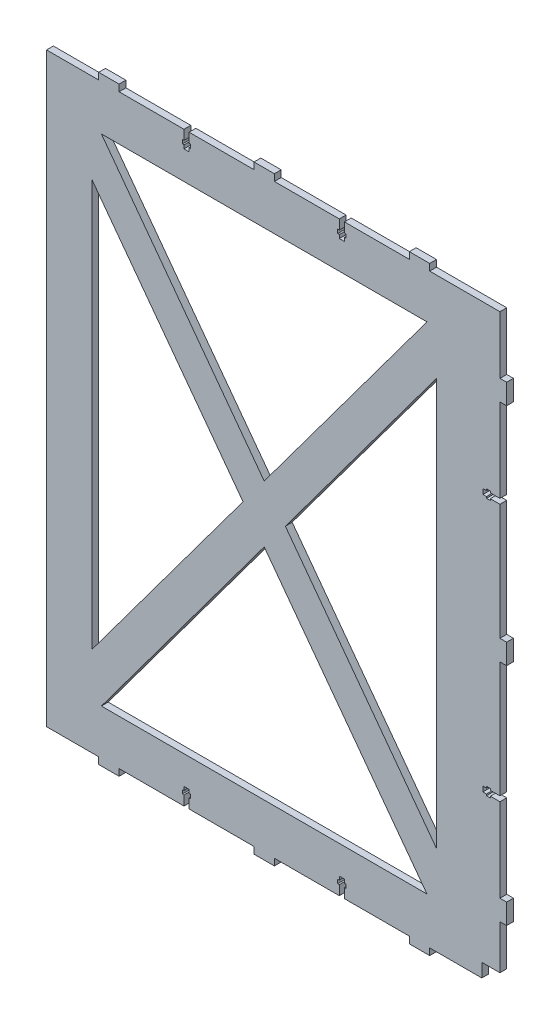
SolidWorks part; units mm, degrees
ref_plane "Спереди" through (0, 0, 0) normal (0, 0, 1) x (1, 0, 0)
ref_plane "Сверху" through (0, 0, 0) normal (0, 1, 0) x (1, 0, 0)
ref_plane "Справа" through (0, 0, 0) normal (1, 0, 0) x (0, 0, -1)
sketch "Эскиз1" plane through (0, 0, 0) normal (0, 0, 1) x (1, 0, 0)
  line L0 (624.2, 179.5716) -> (490.7832, -0.1)
  line L1 (664.2, 258.6) -> (280, 258.6)
  line L2 (664.2, 258.6) -> (664.2, -258.8)
  line L3 (664.2, -258.8) -> (280, -258.8)
  line L4 (280, 258.6) -> (280, -258.8)
  line L5 (615.8144, 218.6) -> (472.1, 25.0606)
  line L6 (615.8144, 218.6) -> (328.3856, 218.6)
  line L7 (624.2, 179.5716) -> (624.2, -179.7716)
  line L8 (615.8144, -218.8) -> (328.3856, -218.8)
  line L9 (320, 179.5716) -> (320, -179.7716)
  line L10 (624.2, -179.7716) -> (490.7832, -0.1)
  line L11 (615.8144, -218.8) -> (472.1, -25.2606)
  line L12 (472.1, 25.0606) -> (328.3856, 218.6)
  line L13 (453.4168, -0.1) -> (320, 179.5716)
  line L14 (453.4168, -0.1) -> (320, -179.7716)
  line L15 (472.1, -25.2606) -> (328.3856, -218.8)
  line L16 (620.0072, 199.0858) -> (664.2, 258.6) construction
  line L17 (490.7832, -0.1) -> (453.4168, -0.1) construction
  line L18 (472.1, 25.0606) -> (472.1, -25.2606) construction
  line L19 (624.2, 179.5716) -> (615.8144, 218.6) construction
  line L20 (320, -179.7716) -> (328.3856, -218.8) construction
  line L21 (324.1928, -199.2858) -> (620.0072, 199.0858) construction
  line L22 (328.3856, 218.6) -> (320, 179.5716) construction
  line L23 (624.2, -179.7716) -> (615.8144, -218.8) construction
  line L24 (620.0072, -199.2858) -> (324.1928, 199.0858) construction
  point P20 (472.1, -0.1)
  point P21 (472.1, -0.1)
  point P25 (472.1, -0.1)
  dimension "D1" = 40
  dimension "D2" = 40
  dimension "D3" = 40
  dimension "D4" = 40
  dimension "D5" = 30
extrude "Бобышка-Вытянуть1" add sketch "Эскиз1" along normal blind 6 and the other way blind 0.0001
sketch "Шипы боковой стенки к основаниям — эскиз" plane through (0, 0, 0) normal (0, 0, 1) x (1, 0, 0)
  line L0 (326, -264.7) -> (344, -264.7)
  line L1 (344, -264.7) -> (344, -258.5)
  line L2 (344, -258.5) -> (326, -258.5)
  line L3 (326, -258.5) -> (326, -264.7)
  line L4 (463.1, -264.7) -> (481.1, -264.7)
  line L5 (481.1, -264.7) -> (481.1, -258.5)
  line L6 (481.1, -258.5) -> (463.1, -258.5)
  line L7 (463.1, -258.5) -> (463.1, -264.7)
  line L8 (600.2, -264.7) -> (618.2, -264.7)
  line L9 (618.2, -264.7) -> (618.2, -258.5)
  line L10 (618.2, -258.5) -> (600.2, -258.5)
  line L11 (600.2, -258.5) -> (600.2, -264.7)
  line L12 (326, 258.3) -> (344, 258.3)
  line L13 (344, 258.3) -> (344, 264.5)
  line L14 (344, 264.5) -> (326, 264.5)
  line L15 (326, 264.5) -> (326, 258.3)
  line L16 (463.1, 258.3) -> (481.1, 258.3)
  line L17 (481.1, 258.3) -> (481.1, 264.5)
  line L18 (481.1, 264.5) -> (463.1, 264.5)
  line L19 (463.1, 264.5) -> (463.1, 258.3)
  line L20 (600.2, 258.3) -> (618.2, 258.3)
  line L21 (618.2, 258.3) -> (618.2, 264.5)
  line L22 (618.2, 264.5) -> (600.2, 264.5)
  line L23 (600.2, 264.5) -> (600.2, 258.3)
  dimension "X001" = 326
  dimension "X002" = 344
  dimension "X003" = 463.1
  dimension "X004" = 481.1
  dimension "X005" = 600.2
  dimension "X006" = 618.2
  dimension "Y001" = 264.7
  dimension "Y002" = 258.5
  dimension "Y003" = 258.3
  dimension "Y004" = 264.5
extrude "Шипы боковой стенки к основаниям" add sketch "Шипы боковой стенки к основаниям — эскиз" along normal blind 6
sketch "Карманные стяжки М4 к основаниям — эскиз" plane through (0, 0, 0) normal (0, 0, 1) x (1, 0, 0)
  line L0 (401.3, -259.8) -> (405.8, -259.8)
  line L1 (405.8, -259.8) -> (405.8, -250.3)
  line L2 (405.8, -250.3) -> (407.2, -250.3)
  line L3 (407.2, -250.3) -> (407.2, -246.9)
  line L4 (407.2, -246.9) -> (405.8, -246.9)
  line L5 (405.8, -246.9) -> (405.8, -243.8)
  line L6 (405.8, -243.8) -> (401.3, -243.8)
  line L7 (401.3, -243.8) -> (401.3, -246.9)
  line L8 (401.3, -246.9) -> (399.9, -246.9)
  line L9 (399.9, -246.9) -> (399.9, -250.3)
  line L10 (399.9, -250.3) -> (401.3, -250.3)
  line L11 (401.3, -250.3) -> (401.3, -259.8)
  line L12 (538.4, -259.8) -> (542.9, -259.8)
  line L13 (542.9, -259.8) -> (542.9, -250.3)
  line L14 (542.9, -250.3) -> (544.3, -250.3)
  line L15 (544.3, -250.3) -> (544.3, -246.9)
  line L16 (544.3, -246.9) -> (542.9, -246.9)
  line L17 (542.9, -246.9) -> (542.9, -243.8)
  line L18 (542.9, -243.8) -> (538.4, -243.8)
  line L19 (538.4, -243.8) -> (538.4, -246.9)
  line L20 (538.4, -246.9) -> (537, -246.9)
  line L21 (537, -246.9) -> (537, -250.3)
  line L22 (537, -250.3) -> (538.4, -250.3)
  line L23 (538.4, -250.3) -> (538.4, -259.8)
  line L24 (401.3, 259.6) -> (405.8, 259.6)
  line L25 (405.8, 259.6) -> (405.8, 250.1)
  line L26 (405.8, 250.1) -> (407.2, 250.1)
  line L27 (407.2, 250.1) -> (407.2, 246.7)
  line L28 (407.2, 246.7) -> (405.8, 246.7)
  line L29 (405.8, 246.7) -> (405.8, 243.6)
  line L30 (405.8, 243.6) -> (401.3, 243.6)
  line L31 (401.3, 243.6) -> (401.3, 246.7)
  line L32 (401.3, 246.7) -> (399.9, 246.7)
  line L33 (399.9, 246.7) -> (399.9, 250.1)
  line L34 (399.9, 250.1) -> (401.3, 250.1)
  line L35 (401.3, 250.1) -> (401.3, 259.6)
  line L36 (538.4, 259.6) -> (542.9, 259.6)
  line L37 (542.9, 259.6) -> (542.9, 250.1)
  line L38 (542.9, 250.1) -> (544.3, 250.1)
  line L39 (544.3, 250.1) -> (544.3, 246.7)
  line L40 (544.3, 246.7) -> (542.9, 246.7)
  line L41 (542.9, 246.7) -> (542.9, 243.6)
  line L42 (542.9, 243.6) -> (538.4, 243.6)
  line L43 (538.4, 243.6) -> (538.4, 246.7)
  line L44 (538.4, 246.7) -> (537, 246.7)
  line L45 (537, 246.7) -> (537, 250.1)
  line L46 (537, 250.1) -> (538.4, 250.1)
  line L47 (538.4, 250.1) -> (538.4, 259.6)
  dimension "X001" = 399.9
  dimension "X002" = 401.3
  dimension "X003" = 405.8
  dimension "X004" = 407.2
  dimension "X005" = 537
  dimension "X006" = 538.4
  dimension "X007" = 542.9
  dimension "X008" = 544.3
  dimension "Y001" = 259.8
  dimension "Y002" = 250.3
  dimension "Y003" = 246.9
  dimension "Y004" = 243.8
  dimension "Y005" = 243.6
  dimension "Y006" = 246.7
  dimension "Y007" = 250.1
  dimension "Y008" = 259.6
extrude "Карманные стяжки М4 к основаниям" cut sketch "Карманные стяжки М4 к основаниям — эскиз" against normal through all and the other way through all
sketch "Задние стойки боковых стенок — эскиз" plane through (0, 0, 0) normal (0, 0, 1) x (1, 0, 0)
  line L0 (663.2, -246.8) -> (680.2, -246.8)
  line L1 (680.2, -246.8) -> (680.2, 258.6)
  line L2 (680.2, 258.6) -> (663.2, 258.6)
  line L3 (663.2, 258.6) -> (663.2, -246.8)
  dimension "X001" = 663.2
  dimension "X002" = 680.2
  dimension "Y001" = 246.8
  dimension "Y002" = 258.6
extrude "Задние стойки боковых стенок" add sketch "Задние стойки боковых стенок — эскиз" along normal blind 6
sketch "Задние шипы боковой стенки — эскиз" plane through (0, 0, 0) normal (0, 0, 1) x (1, 0, 0)
  line L0 (679.9, -207.8) -> (686.1, -207.8)
  line L1 (686.1, -207.8) -> (686.1, -189.8)
  line L2 (686.1, -189.8) -> (679.9, -189.8)
  line L3 (679.9, -189.8) -> (679.9, -207.8)
  line L4 (679.9, -9.1) -> (686.1, -9.1)
  line L5 (686.1, -9.1) -> (686.1, 8.9)
  line L6 (686.1, 8.9) -> (679.9, 8.9)
  line L7 (679.9, 8.9) -> (679.9, -9.1)
  line L8 (679.9, 189.6) -> (686.1, 189.6)
  line L9 (686.1, 189.6) -> (686.1, 207.6)
  line L10 (686.1, 207.6) -> (679.9, 207.6)
  line L11 (679.9, 207.6) -> (679.9, 189.6)
  dimension "X001" = 679.9
  dimension "X002" = 686.1
  dimension "Y001" = 207.8
  dimension "Y002" = 189.8
  dimension "Y003" = 9.1
  dimension "Y004" = 8.9
  dimension "Y005" = 189.6
  dimension "Y006" = 207.6
extrude "Задние шипы боковой стенки" add sketch "Задние шипы боковой стенки — эскиз" along normal blind 6
sketch "Стяжки М4 к задней стенке — эскиз" plane through (0, 0, 0) normal (0, 0, 1) x (1, 0, 0)
  line L0 (681.2, -116.05) -> (681.2, -111.55)
  line L1 (681.2, -111.55) -> (671.7, -111.55)
  line L2 (671.7, -111.55) -> (671.7, -110.15)
  line L3 (671.7, -110.15) -> (668.3, -110.15)
  line L4 (668.3, -110.15) -> (668.3, -111.55)
  line L5 (668.3, -111.55) -> (665.2, -111.55)
  line L6 (665.2, -111.55) -> (665.2, -116.05)
  line L7 (665.2, -116.05) -> (668.3, -116.05)
  line L8 (668.3, -116.05) -> (668.3, -117.45)
  line L9 (668.3, -117.45) -> (671.7, -117.45)
  line L10 (671.7, -117.45) -> (671.7, -116.05)
  line L11 (671.7, -116.05) -> (681.2, -116.05)
  line L12 (681.2, 111.35) -> (681.2, 115.85)
  line L13 (681.2, 115.85) -> (671.7, 115.85)
  line L14 (671.7, 115.85) -> (671.7, 117.25)
  line L15 (671.7, 117.25) -> (668.3, 117.25)
  line L16 (668.3, 117.25) -> (668.3, 115.85)
  line L17 (668.3, 115.85) -> (665.2, 115.85)
  line L18 (665.2, 115.85) -> (665.2, 111.35)
  line L19 (665.2, 111.35) -> (668.3, 111.35)
  line L20 (668.3, 111.35) -> (668.3, 109.95)
  line L21 (668.3, 109.95) -> (671.7, 109.95)
  line L22 (671.7, 109.95) -> (671.7, 111.35)
  line L23 (671.7, 111.35) -> (681.2, 111.35)
  dimension "X001" = 665.2
  dimension "X002" = 668.3
  dimension "X003" = 671.7
  dimension "X004" = 681.2
  dimension "Y001" = 117.45
  dimension "Y002" = 116.05
  dimension "Y003" = 111.55
  dimension "Y004" = 110.15
  dimension "Y005" = 109.95
  dimension "Y006" = 111.35
  dimension "Y007" = 115.85
  dimension "Y008" = 117.25
extrude "Стяжки М4 к задней стенке" cut sketch "Стяжки М4 к задней стенке — эскиз" against normal through all and the other way through all
equation "\"Глубина груза\" = 240"
equation "\"Глубина ячейки\" = \"Глубина груза\" + 10"
equation "\"Мотор Y высота корпуса\" = 42.3"
equation "\"Переднее удлинение полозьев\" = 16.2"
equation "\"Зазор полозьев от задней стенки\" = 10"
equation "\"Удлинение платформы по глубине\" = \"Переднее удлинение полозьев\"+\"Зазор полозьев от задней стенки\"+15.7"
equation "\"Глубина каретки\" = \"Глубина ячейки\" + 30 + \"Мотор Y высота корпуса\" + 20 + \"Удлинение платформы по глубине\""
equation "\"Середина глубины боковой стенки\" = \"Глубина ячейки\"+30.000000000003+\"Глубина каретки\"/2"
equation "\"Плоскость низа боковой стенки\" = -258.800000000018"
equation "\"Плоскость верха боковой стенки\" = 258.599999999984"
equation "\"Проход под болт М4\" = 4.5"
equation "\"Ширина кармана гайки М4\" = 7.3"
equation "\"X001@Шипы боковой стенки к основаниям — эскиз\" = (1*(\"Середина глубины боковой стенки\"+-1*(\"Глубина каретки\"/2-55)-9))"
equation "\"X002@Шипы боковой стенки к основаниям — эскиз\" = (1*(\"Середина глубины боковой стенки\"+-1*(\"Глубина каретки\"/2-55)+9))"
equation "\"X003@Шипы боковой стенки к основаниям — эскиз\" = (1*(\"Середина глубины боковой стенки\"+0*(\"Глубина каретки\"/2-55)-9))"
equation "\"X004@Шипы боковой стенки к основаниям — эскиз\" = (1*(\"Середина глубины боковой стенки\"+0*(\"Глубина каретки\"/2-55)+9))"
equation "\"X005@Шипы боковой стенки к основаниям — эскиз\" = (1*(\"Середина глубины боковой стенки\"+1*(\"Глубина каретки\"/2-55)-9))"
equation "\"X006@Шипы боковой стенки к основаниям — эскиз\" = (1*(\"Середина глубины боковой стенки\"+1*(\"Глубина каретки\"/2-55)+9))"
equation "\"Y001@Шипы боковой стенки к основаниям — эскиз\" = -(1*(\"Плоскость низа боковой стенки\"+(-5.90000000000002)))"
equation "\"Y002@Шипы боковой стенки к основаниям — эскиз\" = -(1*(\"Плоскость низа боковой стенки\"+(0.300000000000022)))"
equation "\"Y003@Шипы боковой стенки к основаниям — эскиз\" = (1*(\"Плоскость верха боковой стенки\"+(-0.300000000000022)))"
equation "\"Y004@Шипы боковой стенки к основаниям — эскиз\" = (1*(\"Плоскость верха боковой стенки\"+(5.90000000000002)))"
equation "\"X001@Карманные стяжки М4 к основаниям — эскиз\" = (1*(\"Середина глубины боковой стенки\"+-1*(\"Глубина каретки\"/2-55)/2-\"Ширина кармана гайки М4\"/2))"
equation "\"X002@Карманные стяжки М4 к основаниям — эскиз\" = (1*(\"Середина глубины боковой стенки\"+-1*(\"Глубина каретки\"/2-55)/2-\"Проход под болт М4\"/2))"
equation "\"X003@Карманные стяжки М4 к основаниям — эскиз\" = (1*(\"Середина глубины боковой стенки\"+-1*(\"Глубина каретки\"/2-55)/2+\"Проход под болт М4\"/2))"
equation "\"X004@Карманные стяжки М4 к основаниям — эскиз\" = (1*(\"Середина глубины боковой стенки\"+-1*(\"Глубина каретки\"/2-55)/2+\"Ширина кармана гайки М4\"/2))"
equation "\"X005@Карманные стяжки М4 к основаниям — эскиз\" = (1*(\"Середина глубины боковой стенки\"+1*(\"Глубина каретки\"/2-55)/2-\"Ширина кармана гайки М4\"/2))"
equation "\"X006@Карманные стяжки М4 к основаниям — эскиз\" = (1*(\"Середина глубины боковой стенки\"+1*(\"Глубина каретки\"/2-55)/2-\"Проход под болт М4\"/2))"
equation "\"X007@Карманные стяжки М4 к основаниям — эскиз\" = (1*(\"Середина глубины боковой стенки\"+1*(\"Глубина каретки\"/2-55)/2+\"Проход под болт М4\"/2))"
equation "\"X008@Карманные стяжки М4 к основаниям — эскиз\" = (1*(\"Середина глубины боковой стенки\"+1*(\"Глубина каретки\"/2-55)/2+\"Ширина кармана гайки М4\"/2))"
equation "\"Y001@Карманные стяжки М4 к основаниям — эскиз\" = -(1*(\"Плоскость низа боковой стенки\"+(-1)))"
equation "\"Y002@Карманные стяжки М4 к основаниям — эскиз\" = -(1*(\"Плоскость низа боковой стенки\"+(8.50000000000001)))"
equation "\"Y003@Карманные стяжки М4 к основаниям — эскиз\" = -(1*(\"Плоскость низа боковой стенки\"+(11.9)))"
equation "\"Y004@Карманные стяжки М4 к основаниям — эскиз\" = -(1*(\"Плоскость низа боковой стенки\"+(15)))"
equation "\"Y005@Карманные стяжки М4 к основаниям — эскиз\" = (1*(\"Плоскость верха боковой стенки\"+(-15)))"
equation "\"Y006@Карманные стяжки М4 к основаниям — эскиз\" = (1*(\"Плоскость верха боковой стенки\"+(-11.9)))"
equation "\"Y007@Карманные стяжки М4 к основаниям — эскиз\" = (1*(\"Плоскость верха боковой стенки\"+(-8.50000000000001)))"
equation "\"Y008@Карманные стяжки М4 к основаниям — эскиз\" = (1*(\"Плоскость верха боковой стенки\"+(1)))"
